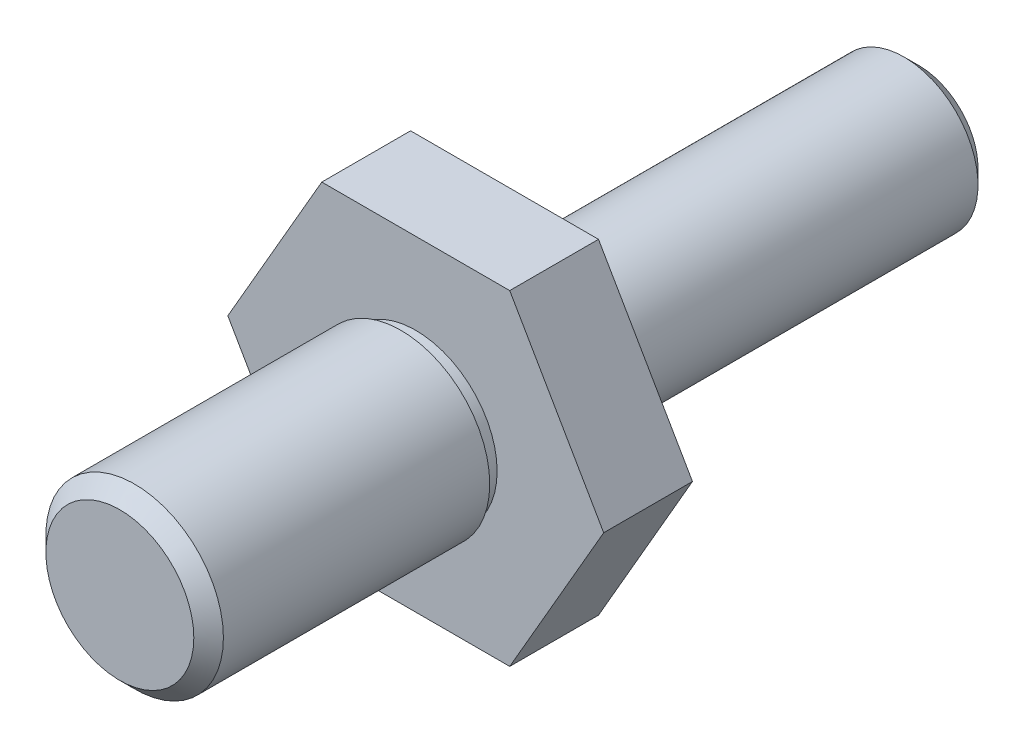
SolidWorks part; units mm, degrees
ref_plane "前视基准面" through (0, 0, 0) normal (0, 0, 1) x (1, 0, 0)
ref_plane "上视基准面" through (0, 0, 0) normal (0, 1, 0) x (1, 0, 0)
ref_plane "右视基准面" through (0, 0, 0) normal (1, 0, 0) x (0, 0, -1)
sketch "草图1" plane through (0, 0, 0) normal (0, 0, 1) x (1, 0, 0)
  circle A0 centre (0, 0) radius 6
  dimension "D1" = 12
extrude "凸台-拉伸1" add sketch "草图1" along normal blind 20
cosmetic thread "装饰螺纹线1" parameters "D2"=11
sketch "草图2" plane through (0, 0, 0) normal (0, 0, -1) x (-1, 0, 0)
  line L0 (0, 0) -> (4.9701, 0) construction
  line L1 (6.3509, 11) -> (-6.3509, 11)
  line L2 (-6.3509, 11) -> (-12.7017, 0)
  line L3 (-12.7017, 0) -> (-6.3509, -11)
  line L4 (-6.3509, -11) -> (6.3509, -11)
  line L5 (6.3509, -11) -> (12.7017, 0)
  line L6 (12.7017, 0) -> (6.3509, 11)
  circle A0 centre (0, 0) radius 11 construction
  dimension "D1" = 22
extrude "凸台-拉伸2" add sketch "草图2" along normal blind 6
sketch "草图3" plane through (0, 0, -6) normal (0, 0, -1) x (-1, 0, 0)
  circle A0 centre (0, 0) radius 7.5
  dimension "D1" = 15
extrude "凸台-拉伸3" add sketch "草图3" along normal blind 1.5
sketch "草图4" plane through (0, 0, -7.5) normal (0, 0, -1) x (-1, 0, 0)
  circle A0 centre (0, 0) radius 5
  dimension "D1" = 10
extrude "凸台-拉伸4" add sketch "草图4" along normal blind 26.5
sketch "草图6" plane through (0, 0, 0) normal (0, 0, 1) x (1, 0, 0)
  circle A0 centre (0, 0) radius 6
  circle A2 centre (0, 0) radius 5.5
  circle A3 centre (0, 0) radius 6 construction
  dimension "D1" = 0.5
extrude "切除-拉伸1" cut sketch "草图6" along normal blind 1
hole_wizard "M5x0.8 螺纹孔1" positions "草图9" profile "草图8" tap size "M5x0.8" standard "JIS"
sketch "草图9" plane through (0, 0, -34) normal (0, 0, -1) x (-1, 0, 0)
  point P1 (0, 0)
sketch "草图8" plane through (0, 0, -34) normal (1, 0, 0) x (0, 1, 0)
  line L0 (0, 0) -> (0, 13.6618)
  line L1 (0, 13.6618) -> (2.1, 12.4)
  line L2 (2.1, 12.4) -> (2.1, 0)
  line L5 (2.1, 0) -> (0, 0)
  line L10 (0, 13.6618) -> (-2.1, 12.4) construction
  line L11 (0, -6.35) -> (0, 107.95) construction
  dimension "螺纹孔钻头直径" = 4.2
  dimension "螺纹孔钻头深度" = 12.4
  dimension "导头角度" = 118
cosmetic thread "孔螺蚊线1" parameters "D1"=10, "D2"=5
chamfer "倒角1" distance 1 angle 45 2 edges at (-5, 0, -34) (6, 0, 20)
